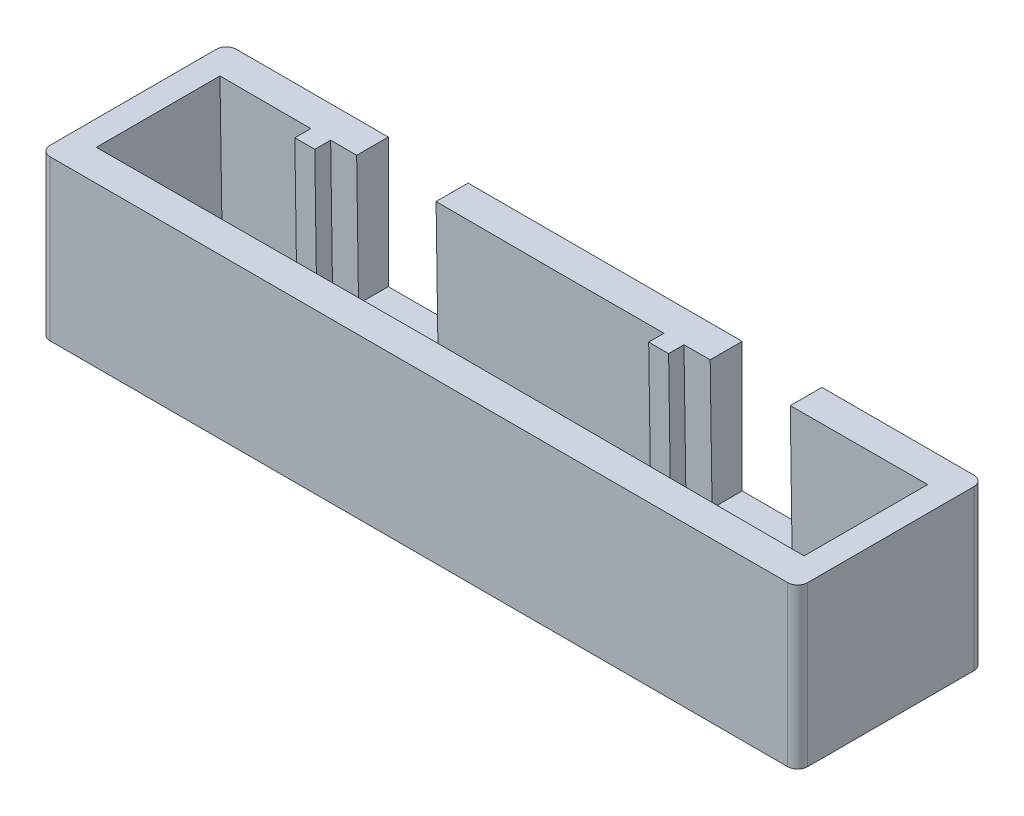
SolidWorks part; units mm, degrees
ref_plane "Front" through (0, 0, 0) normal (0, 0, 1) x (1, 0, 0)
ref_plane "Top" through (0, 0, 0) normal (0, 1, 0) x (1, 0, 0)
ref_plane "Right" through (0, 0, 0) normal (1, 0, 0) x (0, 0, -1)
sketch "Sketch15" plane through (0, 0, 0) normal (0, 1, 0) x (1, 0, 0)
  line L0 (-19, -4.67) -> (19, 4.67) construction
  line L1 (-19, 4.67) -> (19, 4.67)
  line L2 (-19, 4.67) -> (-19, -4.67)
  line L3 (-19, -4.67) -> (19, -4.67)
  line L4 (19, 4.67) -> (19, -4.67)
  point P4 (0, 0)
  dimension "D1" = 38
  dimension "D2" = 9.34
extrude "Boss-Extrude11" add sketch "Sketch15" along normal blind 1.5
sketch "Sketch16" plane through (0, 1.5, 0) normal (0, 1, 0) x (1, 0, 0)
  line L4 (-19, 4.67) -> (-19, -4.67)
  line L5 (-19, -4.67) -> (19, -4.67)
  line L6 (19, -4.67) -> (19, 4.67)
  line L7 (19, 4.67) -> (-19, 4.67)
  line L8 (-19, 4.67) -> (-19, -4.67)
  line L9 (-19, -4.67) -> (19, -4.67)
  line L10 (19, -4.67) -> (19, 4.67)
  line L11 (19, 4.67) -> (-19, 4.67)
  dimension "D1" = 0
sketch "Sketch5" plane through (0, 1.5, 0) normal (0, 1, 0) x (1, 0, 0)
  line L0 (0, 9.7513) -> (0, 0) construction
  line L1 (0, 0) -> (6.8181, 0) construction
  line L2 (-17.75, 3.2) -> (-17.75, -3.2)
  line L3 (17.75, 3.2) -> (17.75, -3.2)
  line L4 (-17.75, 3.2) -> (-21.2737, 3.2) construction
  line L5 (17.75, 3.2) -> (20.5508, 3.2) construction
  line L6 (-13.185, 3.5859) -> (-13.185, 2.3859) construction
  line L7 (-13.185, 2.3859) -> (-12.185, 2.3859) construction
  line L8 (-12.185, 2.3859) -> (-12.185, 3.5859) construction
  line L9 (-13.185, 3.5859) -> (-12.185, 3.5859) construction
  line L10 (-12.685, 5.547) -> (-12.685, 3.954) construction
  spline S0 degree 3 poles (-17.75, 3.2) (-14.75, 3.2) (0, 3.1) (14.75, 3.2) (17.75, 3.2) knots 0 0 0 0 0.5 1 1 1 1
  spline S1 degree 3 poles (-17.75, -3.2) (-14.75, -3.2) (0, -3.1) (14.75, -3.2) (17.75, -3.2) knots 0 0 0 0 0.5 1 1 1 1
  point P9 (-13.185, 3.1859)
  dimension "D7" = 9
  dimension "D8" = 9
  dimension "D1" = 35.5
  dimension "D2" = 6.4
  dimension "D3" = 6.3
  dimension "D4" = 1
  dimension "D5" = 0.8
  dimension "D6" = 12.685
  dimension "D9" = 1.2
extrude "Boss-Extrude12" add sketch "Sketch16" along normal blind 6.5
sketch "Sketch6" plane through (0, 8, 0) normal (0, 1, 0) x (1, 0, 0)
  line L0 (0, 10.4752) -> (0, 0) construction
  line L1 (0, 0) -> (14.3147, 0) construction
  line L2 (-17.75, 3.1) -> (-17.75, -3.1)
  line L3 (17.75, 3.1) -> (17.75, -3.1)
  line L6 (-17.75, 3.2) -> (-17.75, -3.2) construction
  line L7 (17.75, 3.2) -> (17.75, -3.2) construction
  line L8 (17.75, 3.1) -> (24.3903, 3.1) construction
  line L9 (-17.75, 3.1) -> (-21.112, 3.1) construction
  spline S0 degree 3 poles (-17.75, 3.1) (-11.8332, 3.1) (0.0002, 3) (11.8329, 3.1) (17.75, 3.1) knots 0 0 0 0 0.5 1 1 1 1
  spline S1 degree 3 poles (-17.75, -3.1) (-11.8332, -3.1) (0.0002, -3) (11.8329, -3.1) (17.75, -3.1) knots 0 0 0 0 0.5 1 1 1 1
  dimension "D1" = 6.1
  dimension "D2" = 6.2
sketch "Sketch10" plane through (0, 8, 0) normal (0, 1, 0) x (1, 0, 0)
  line L0 (-8.875, 8.9211) -> (-8.875, 0) construction
  line L1 (-10.875, 4.67) -> (-6.875, 4.67)
  line L2 (-10.875, 4.67) -> (-10.875, 2.67)
  line L3 (-10.875, 2.67) -> (-6.875, 2.67)
  line L4 (-6.875, 4.67) -> (-6.875, 2.67)
  line L5 (-8.875, 0) -> (0, 0) construction
  line L7 (0, 0) -> (0, 7.9605) construction
  line L8 (10.875, 4.67) -> (10.875, 2.67)
  line L9 (10.875, 4.67) -> (6.875, 4.67)
  line L10 (6.875, 4.67) -> (6.875, 2.67)
  line L11 (10.875, 2.67) -> (6.875, 2.67)
  line L12 (19, 4.67) -> (-19, 4.67) construction
  dimension "D1" = 4
  dimension "D2" = 2
  dimension "D3" = 8.875
loft "Cut-Loft1" cut profiles "Sketch5", "Sketch6"
sketch "Sketch8" plane through (0, 1.5, 0) normal (0, 1, 0) x (1, 0, 0)
  line L0 (-13.185, 2.3859) -> (-12.185, 2.3859) construction
  line L1 (-12.185, 2.3859) -> (-12.185, 3.5859) construction
  line L2 (-13.185, 3.5859) -> (-12.185, 3.5859) construction
  line L3 (-13.185, 3.5859) -> (-13.185, 2.3859) construction
  line L4 (-13.185, 2.3859) -> (-12.185, 2.3859)
  line L5 (-12.185, 2.3859) -> (-12.185, 3.5859)
  line L6 (-13.185, 3.5859) -> (-12.185, 3.5859)
  line L7 (-13.185, 3.5859) -> (-13.185, 2.3859)
sketch "Sketch9" plane through (0, 8, 0) normal (0, 1, 0) x (1, 0, 0)
  line L0 (-13.185, 3.5859) -> (-13.185, 2.3859) construction
  line L2 (-13.185, 3.4918) -> (-13.185, 2.2918)
  line L3 (-12.185, 2.3859) -> (-12.185, 3.5859) construction
  line L4 (-12.185, 2.2918) -> (-12.185, 3.4918)
  line L5 (-13.185, 2.2918) -> (-12.185, 2.2918)
  line L6 (-12.185, 3.4918) -> (-13.185, 3.4918)
  spline S0 degree 3 poles (-17.75, 3.1) (-11.8332, 3.1) (0.0002, 3) (11.8329, 3.1) (17.75, 3.1) knots 0 0 0 0 0.5 1 1 1 1 construction
  point P5 (-13.185, 3.0918)
  dimension "D1" = 0.8
loft "Loft1" add profiles "Sketch8", "Sketch9"
pattern_linear "LPattern2" count 2 spacing 17.75 along (1, 0, 0) of "Loft1"
extrude "Cut-Extrude2" cut sketch "Sketch10" against normal up to surface (6.5 mm away) up to face at (-2.7067, 1.5, -1.8522)
sketch "Sketch2" plane through (0, 1.5, 0) normal (0, 1, 0) x (1, 0, 0)
  line L0 (-8.875, 8.0945) -> (-8.875, 0) construction
  line L1 (-13.955, -1.27) -> (-3.795, 1.27) construction
  line L2 (-13.955, 1.27) -> (-3.795, 1.27) construction
  line L3 (-13.955, 1.27) -> (-13.955, -1.27) construction
  line L4 (-13.955, -1.27) -> (-3.795, -1.27) construction
  line L5 (-3.795, 1.27) -> (-3.795, -1.27) construction
  line L24 (-8.875, 0) -> (0, 0) construction
  line L31 (-4.195, -0.87) -> (-4.195, -1.67)
  line L32 (-4.195, -1.67) -> (-3.395, -1.67)
  line L33 (-3.395, -1.67) -> (-3.395, -0.87)
  line L34 (-3.395, -0.87) -> (-4.195, -0.87)
  line L35 (-4.195, -0.87) -> (-3.395, -1.67) construction
  line L36 (-4.195, -1.67) -> (-3.395, -0.87) construction
  point P7 (-8.875, 0)
  point P30 (-3.795, -1.27)
  dimension "D1" = 8.875
  dimension "D2" = 10.16
  dimension "D3" = 2.54
  dimension "D9" = 0.8
extrude "Cut-Extrude1" cut sketch "Sketch2" against normal through all contours L33 L34 L31 L32
pattern_linear "LPattern1" count 5 spacing 2.54 along (-1, 0, 0) count 2 spacing 2.54 along (0, 0, -1) of "Cut-Extrude1"
mirror "Mirror1" about plane through (0, 0, 0) normal (1, 0, 0) of "LPattern1", "Cut-Extrude1"
fillet "Fillet6" radius 0.5 4 edges at (-19, 4, 4.67) (-19, 4, -4.67) (19, 4, -4.67) (19, 4, 4.67)
